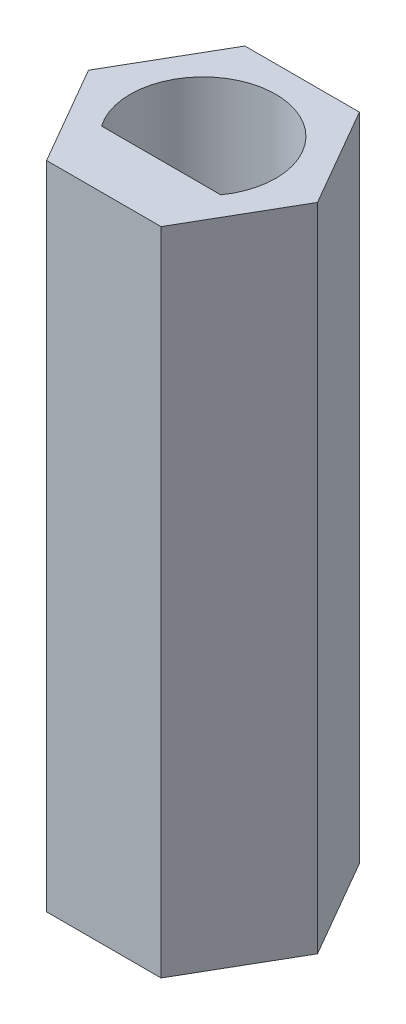
SolidWorks part; units mm, degrees
ref_plane "Alzado" through (0, 0, 0) normal (0, 0, 1) x (1, 0, 0)
ref_plane "Planta" through (0, 0, 0) normal (0, 1, 0) x (1, 0, 0)
ref_plane "Vista lateral" through (0, 0, 0) normal (1, 0, 0) x (0, 0, -1)
sketch "Croquis1" plane through (0, 0, 0) normal (0, 1, 0) x (1, 0, 0)
  line L1 (3.695, 0) -> (1.8475, 3.2)
  line L2 (1.8475, 3.2) -> (-1.8475, 3.2)
  line L3 (-1.8475, 3.2) -> (-3.695, 0)
  line L4 (-3.695, 0) -> (-1.8475, -3.2)
  line L5 (-1.8475, -3.2) -> (1.8475, -3.2)
  line L6 (1.8475, -3.2) -> (3.695, 0)
  circle A0 centre (0, 0) radius 3.2 construction
  dimension "D1" = 6.4
extrude "Saliente-Extruir1" add sketch "Croquis1" along normal blind 28
sketch "Croquis2" plane through (0, 28, 0) normal (0, 1, 0) x (1, 0, 0)
  line L0 (-1.9235, -1.35) -> (1.9235, -1.35)
  arc A0 (1.9235, -1.35) -> (-1.9235, -1.35) centre (0, 0) ccw
  arc A1 (-1.9235, -1.35) -> (1.9235, -1.35) centre (0, 0) ccw construction
  dimension "D1" = 4.7
  dimension "D2" = 3.7
extrude "Cortar-Extruir1" cut sketch "Croquis2" against normal blind 8.3
sketch "Croquis3" plane through (0, 0, 0) normal (0, -1, 0) x (-1, 0, 0)
  circle A0 centre (0, 0) radius 1.5
  dimension "D1" = 3
extrude "Cortar-Extruir2" cut sketch "Croquis3" against normal blind 18
sketch "Croquis4" plane through (0, 0, 0) normal (0, -1, 0) x (1, 0, 0)
  circle A0 centre (0, 0) radius 4
  dimension "D1" = 8
extrude "Cortar-Extruir3" cut sketch "Croquis4" against normal blind 7
equation "\"D1@Croquis1\"=6.6-0.2"
equation "\"D2@Croquis2\"=3.5+0.2"
equation "\"D1@Croquis2\"=4.00+0.7mm"
equation "\"D1@Croquis3\"=2.8+0.2"
